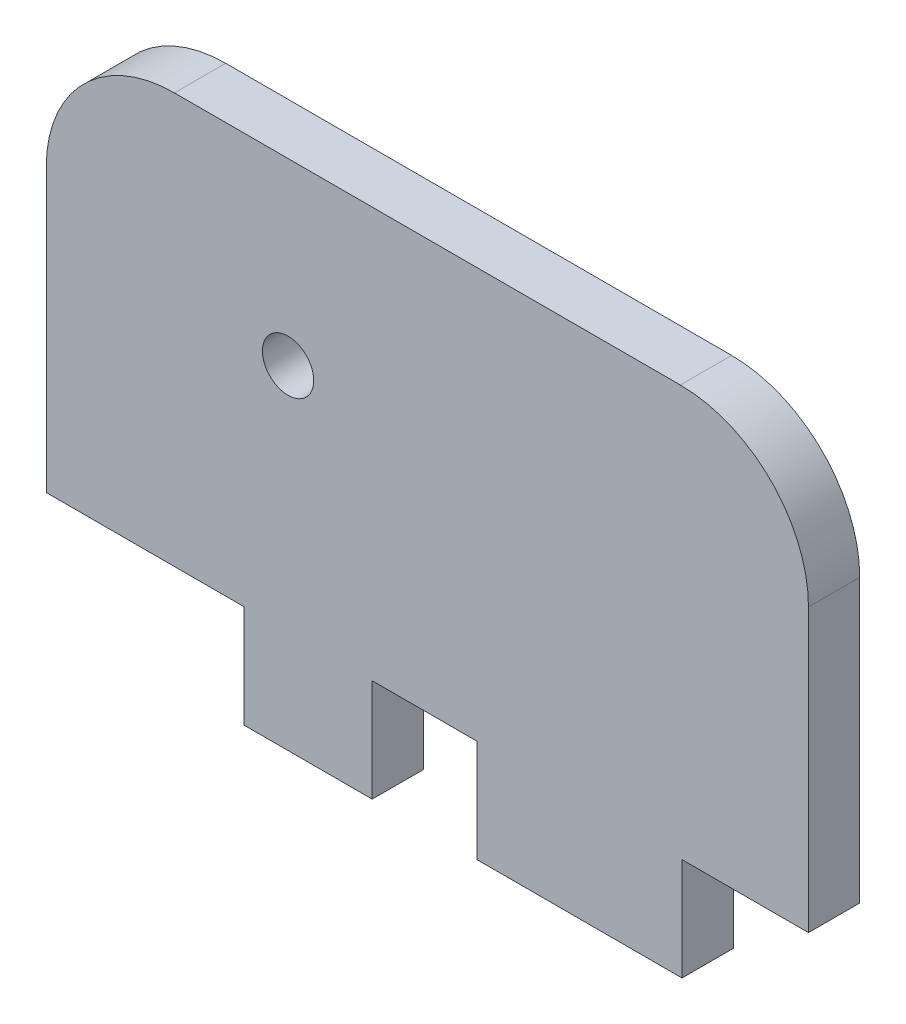
SolidWorks part; units mm, degrees
ref_plane "Front Plane" through (0, 0, 0) normal (0, 0, 1) x (1, 0, 0)
ref_plane "Top Plane" through (0, 0, 0) normal (0, 1, 0) x (1, 0, 0)
ref_plane "Right Plane" through (0, 0, 0) normal (1, 0, 0) x (0, 0, -1)
sketch "Sketch1" plane through (0, 0, 0) normal (0, 0, 1) x (1, 0, 0)
  line L0 (9.9327, -1) -> (14.8658, -1)
  line L1 (1.9327, -1) -> (-2.1519, -1)
  line L2 (-7.1519, -1) -> (-7.1519, -5)
  line L3 (-7.1519, -1) -> (-14.8658, -1)
  line L4 (-7.1519, -5) -> (-2.1519, -5)
  line L5 (-2.1519, -1) -> (-2.1519, -5)
  line L6 (9.9327, -1) -> (9.9327, -5)
  line L7 (9.9327, -5) -> (1.9327, -5)
  line L8 (1.9327, -5) -> (1.9327, -1)
  line L9 (-14.8658, 10) -> (-14.8658, -1)
  line L12 (14.8658, 10) -> (14.8658, -1)
  line L16 (9.8658, 15) -> (-9.8658, 15)
  arc A0 (14.8658, 10) -> (9.8658, 15) centre (9.8658, 10) ccw
  circle A1 centre (-5.4342, 8) radius 1
  arc A2 (-14.8658, 10) -> (-9.8658, 15) centre (-9.8658, 10) cw
  dimension "D1" = 20.3
  dimension "D3" = 4
  dimension "D4" = 2
  dimension "D5" = 11
  dimension "D7" = 9
  dimension "D2" = 5
  dimension "D8" = 19.7317
  dimension "D6" = 4
extrude "Boss-Extrude1" add sketch "Sketch1" along normal blind 2
